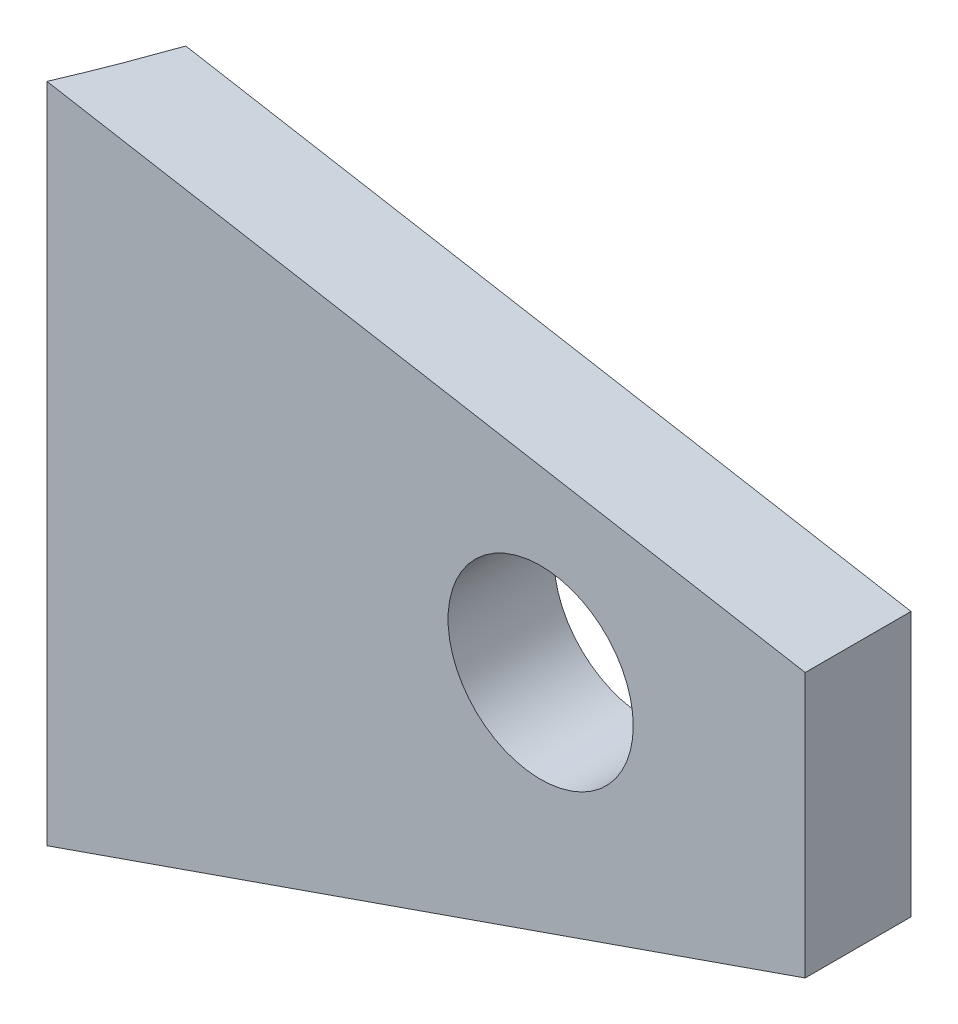
SolidWorks part; units mm, degrees
material "Acrylic (Medium-high impact)"
ref_plane "Front Plane" through (0, 0, 0) normal (0, 0, 1) x (1, 0, 0)
ref_plane "Top Plane" through (0, 0, 0) normal (0, 1, 0) x (1, 0, 0)
ref_plane "Right Plane" through (0, 0, 0) normal (1, 0, 0) x (0, 0, -1)
sketch "Sketch15" plane through (0, 0, 0) normal (0, 0, 1) x (1, 0, 0)
  line L0 (-9.33, 5.01) -> (-9.33, -7.5)
  line L1 (-9.33, -7.5) -> (5, -2.5)
  line L2 (5, -2.5) -> (5, 2.5)
  line L3 (5, 2.5) -> (-9.33, 5.01)
  line L4 (5, 0) -> (0, 0) construction
  line L5 (0, 0) -> (-6, 0) construction
  circle A0 centre (0, 0) radius 1.75
  dimension "D1" = 3.5
  dimension "D2" = 5
  dimension "D3" = 5
  dimension "D4" = 5
  dimension "D5" = 14.33
  dimension "D6" = 5.01
extrude "Boss-Extrude2" add sketch "Sketch15" along normal blind 2
sketch "Sketch16" plane through (0, 0, 0) normal (0, 1, 0) x (1, 0, 0)
  line L0 (5, -2) -> (-9.33, -2) construction
  line L1 (5, -2) -> (-9.33, -2) construction
  line L2 (5, 0) -> (-9.33, 0) construction
  line L3 (5, 0) -> (-9.33, 0) construction
  line L4 (-9.33, 22) -> (14.5779, 22) construction
  circle A0 centre (-44.33, 10) radius 37
  dimension "D2" = 74
  dimension "D1" = 22
extrude "Cut-Extrude1" cut sketch "Sketch16" against normal through all both and the other way through all
